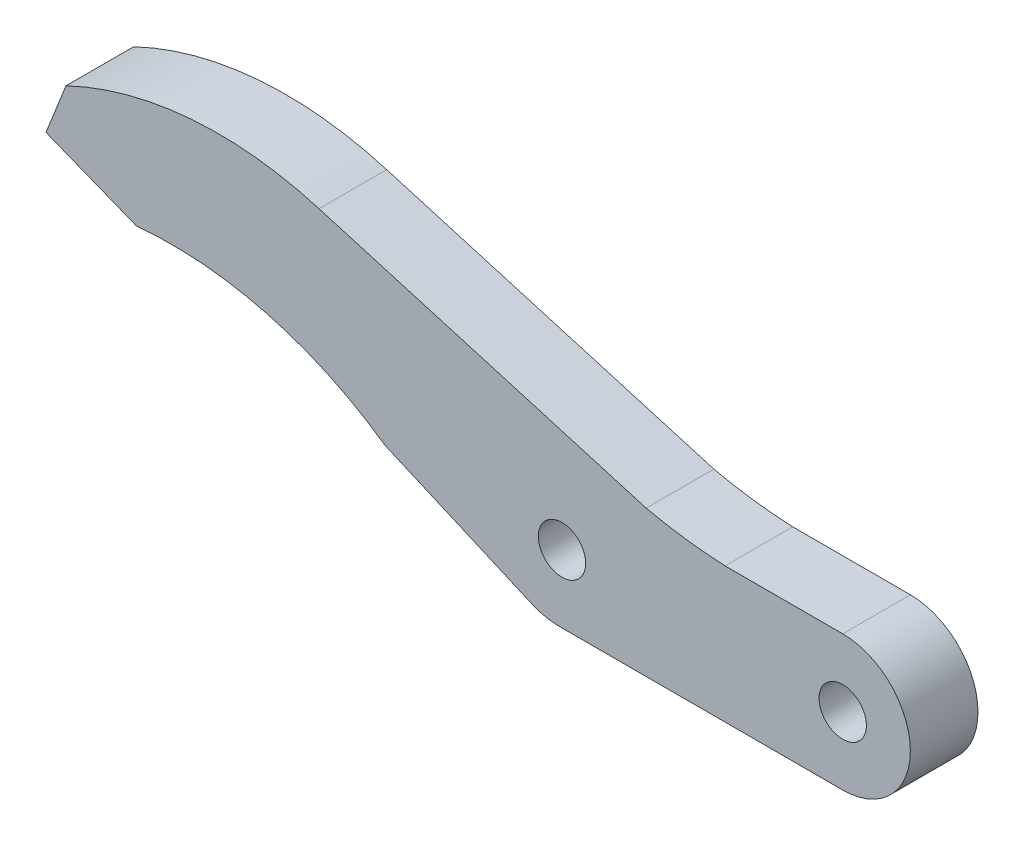
SolidWorks part; units mm, degrees
ref_plane "Front Plane" through (0, 0, 0) normal (0, 0, 1) x (1, 0, 0)
ref_plane "Top Plane" through (0, 0, 0) normal (0, 1, 0) x (1, 0, 0)
ref_plane "Right Plane" through (0, 0, 0) normal (1, 0, 0) x (0, 0, -1)
sketch "Sketch2" plane through (0, 0, 0) normal (0, 0, 1) x (1, 0, 0)
  line L0 (-33.8284, 0.1478) -> (-22, -5)
  line L1 (0, -5) -> (-22, -5)
  line L2 (-52.1984, 5) -> (-58.8916, 7.6535)
  line L3 (-58.8916, 7.6535) -> (-57.4174, 11.3719)
  line L4 (0, 5) -> (-8.7, 5)
  line L6 (-38.7093, 12.8595) -> (-14.5233, 5.7827)
  line L7 (-58.8916, 7.6535) -> (-20.9169, 7.6535) construction
  line L8 (0, 0) -> (-20.75, 0) construction
  circle A0 centre (0, 0) radius 1.75
  arc A1 (0, -5) -> (0, 5) centre (0, 0) ccw
  circle A2 centre (-20.75, 0) radius 1.75
  arc A3 (-33.8284, 0.1478) -> (-52.1984, 5) centre (-49.5655, -22.2319) ccw
  arc A4 (-8.7, 5) -> (-14.5233, 5.7827) centre (-7.1526, 38.5643) cw
  arc A5 (-38.7093, 12.8595) -> (-57.4174, 11.3719) centre (-46.1413, -12.0556) ccw
  dimension "D1" = 5
  dimension "D2" = 3.5
  dimension "D4" = 25.2
  dimension "D6" = 33.6
  dimension "D7" = 26
  dimension "D8" = 27.3589
  dimension "D19" = 3.5
  dimension "D3" = 22
  dimension "D5" = 8.7
  dimension "D9" = 12.9
  dimension "D10" = 7.2
  dimension "D11" = 4
  dimension "D12" = 156.481
  dimension "D13" = 68.374
  dimension "D14" = 163.691
  dimension "D15" = 19
  dimension "D16" = 18.7672
  dimension "D17" = 5.8757
  dimension "D18" = 20.75
extrude "Boss-Extrude1" add sketch "Sketch2" along normal blind 5
fillet "Fillet1" radius 5 1 edges at (-22, -5, 2.5)
ref_point "Point1"
ref_point "Point2"
ref_plane "Plane1" through (0, -15, 0) normal (0, -1, 0) x (-1, 0, 0)
sketch "Sketch3" plane through (0, -15, 0) normal (0, -1, 0) x (-1, 0, 0)
  point P0 (18.7075, -2.837)
